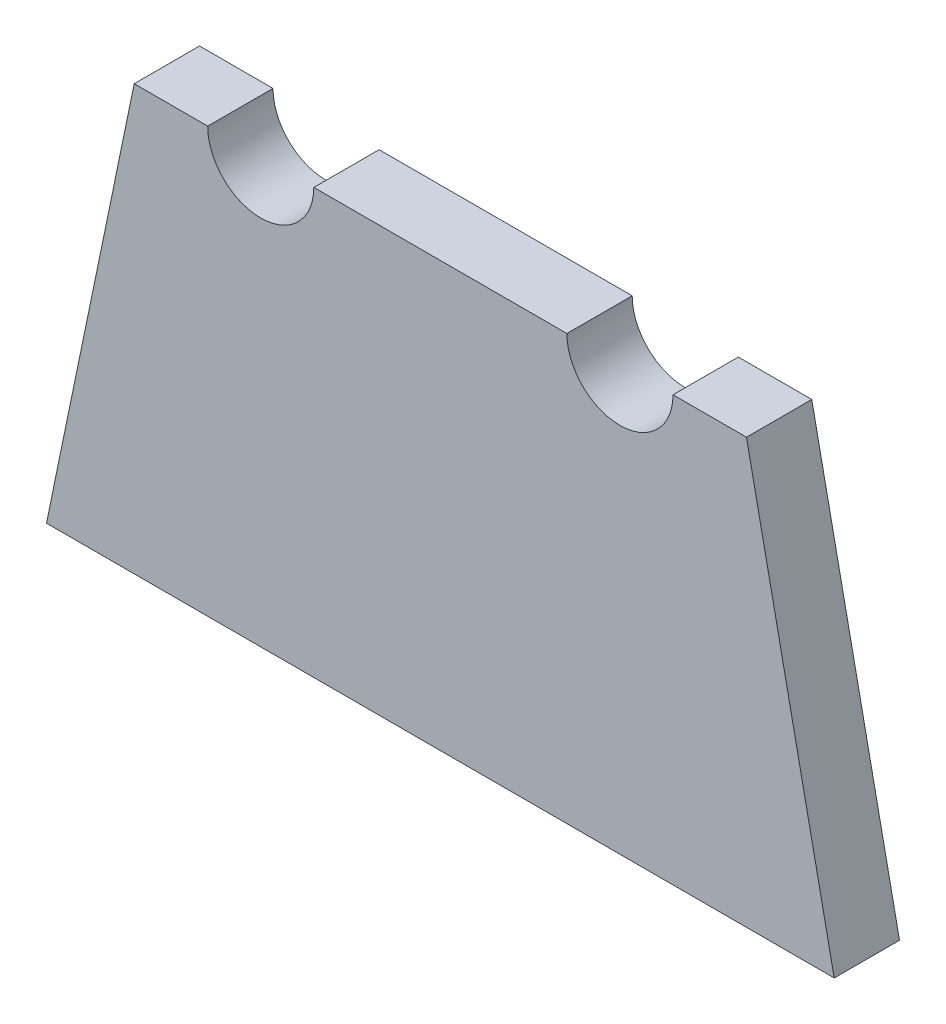
SolidWorks part; units mm, degrees
ref_plane "Спереди" through (0, 0, 0) normal (0, 0, 1) x (1, 0, 0)
ref_plane "Сверху" through (0, 0, 0) normal (0, 1, 0) x (1, 0, 0)
ref_plane "Справа" through (0, 0, 0) normal (1, 0, 0) x (0, 0, -1)
sketch "Sketch1" plane through (0, 0, 0) normal (0, 0, 1) x (1, 0, 0)
  line L0 (4.825, -2.8954) -> (3.75, 2.3046)
  line L1 (3.75, 2.3046) -> (2.85, 2.3046)
  line L2 (-3.75, 2.3046) -> (-4.825, -2.8954)
  line L3 (-4.825, -2.8954) -> (4.825, -2.8954)
  line L4 (0, 2.3637) -> (0, -1.0868) construction
  line L5 (-2.85, 2.3046) -> (-3.75, 2.3046)
  line L6 (1.55, 2.3046) -> (-1.55, 2.3046)
  arc A0 (1.55, 2.3046) -> (2.85, 2.3046) centre (2.2, 2.3046) ccw
  arc A1 (-1.55, 2.3046) -> (-2.85, 2.3046) centre (-2.2, 2.3046) cw
  dimension "D4" = 1.3
  dimension "D1" = 7.5
  dimension "D2" = 9.65
  dimension "D3" = 4.825
  dimension "D6" = 5.2
extrude "Boss-Extrude1" add sketch "Sketch1" along normal blind 0.8
